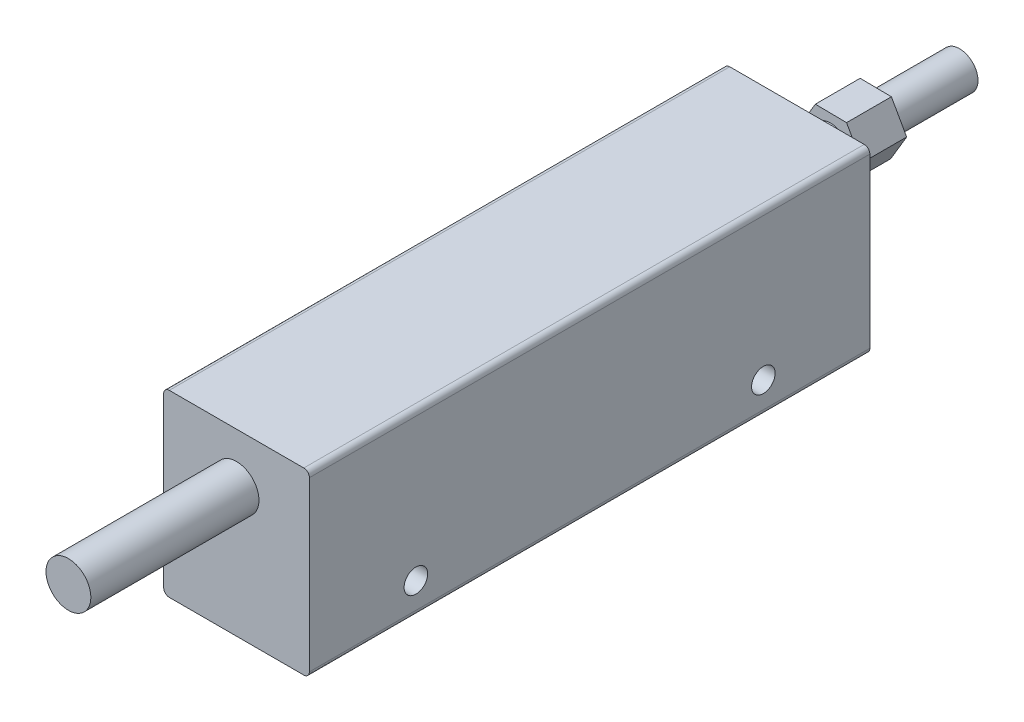
SolidWorks part; units mm, degrees
ref_plane "Front Plane" through (0, 0, 0) normal (0, 0, 1) x (1, 0, 0)
ref_plane "Top Plane" through (0, 0, 0) normal (0, 1, 0) x (1, 0, 0)
ref_plane "Right Plane" through (0, 0, 0) normal (1, 0, 0) x (0, 0, -1)
sketch "Sketch1" plane through (0, 0, 0) normal (0, 0, 1) x (1, 0, 0)
  line L1 (0, 0) -> (13, 0)
  line L2 (0, 0) -> (0, 16)
  line L3 (0, 16) -> (13, 16)
  line L4 (13, 0) -> (13, 16)
  dimension "D1" = 16
  dimension "D2" = 13
extrude "Boss-Extrude1" add sketch "Sketch1" along normal blind 50
sketch "Sketch2" plane through (13, 0, 0) normal (1, 0, 0) x (0, 0, -1)
  line L0 (-50, 0) -> (-50, 16) construction
  line L1 (-50, 0) -> (0, 0) construction
  circle A0 centre (-40.5, 2.8) radius 1.05
  circle A1 centre (-9.5, 2.8) radius 1.05
  dimension "D1" = 2.1
  dimension "D2" = 2.1
  dimension "D3" = 9.5
  dimension "D4" = 31
  dimension "D5" = 2.8
extrude "Cut-Extrude1" cut sketch "Sketch2" against normal through all
sketch "Sketch3" plane through (0, 0, 50) normal (0, 0, 1) x (1, 0, 0)
  line L0 (0, 0) -> (13, 0) construction
  line L1 (13, 16) -> (0, 16) construction
  circle A0 centre (6.5, 11.5) radius 2
  point P7 (6.5, 16)
  dimension "D1" = 4
  dimension "D2" = 11.5
extrude "Boss-Extrude2" add sketch "Sketch3" along normal blind 15
sketch "Sketch4" plane through (0, 0, 0) normal (0, 0, -1) x (-1, 0, 0)
  line L0 (0, 0) -> (-13, 0) construction
  line L1 (-13, 16) -> (0, 16) construction
  circle A0 centre (-6.5, 11.5) radius 1.65
  point P6 (-6.5, 16)
  dimension "D1" = 3.3
  dimension "D2" = 11.5
extrude "Boss-Extrude3" add sketch "Sketch4" along normal blind 14.5
fillet "Fillet1" radius 0.5 4 edges at (13, 0, 25) (0, 0, 25) (13, 16, 25) (0, 16, 25)
sketch "Sketch6" plane through (0, 0, -14.5) normal (0, 0, -1) x (-1, 0, 0)
  line L1 (-7.8622, 9.0703) -> (-5.0769, 9.1054)
  line L2 (-5.0769, 9.1054) -> (-3.7147, 11.5351)
  line L3 (-3.7147, 11.5351) -> (-5.1378, 13.9297)
  line L4 (-5.1378, 13.9297) -> (-7.9231, 13.8946)
  line L5 (-7.9231, 13.8946) -> (-9.2853, 11.4649)
  line L6 (-9.2853, 11.4649) -> (-7.8622, 9.0703)
  circle A0 centre (-6.5, 11.5) radius 2.4123 construction
extrude "Boss-Extrude4" add sketch "Sketch6" against normal blind 4 from offset 7.5 offset against normal yes
equation "\"D1@Boss-Extrude2\"  = 15mm"
equation "\"D1@Boss-Extrude3\"   = 14.5mm"
